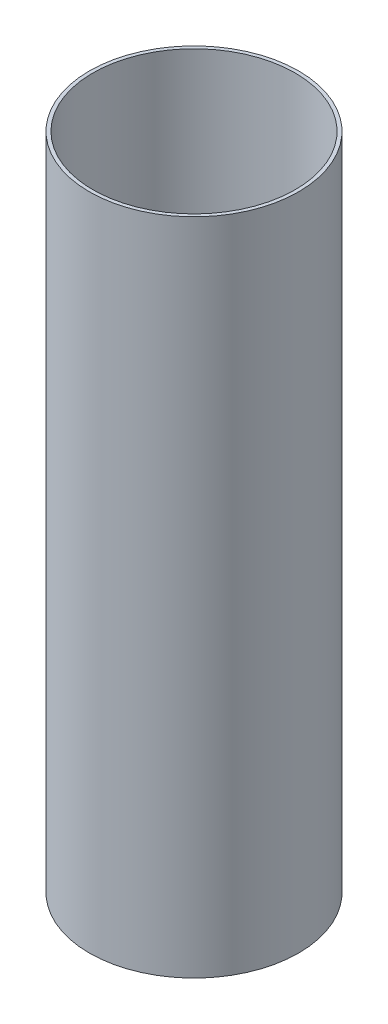
SolidWorks part; units mm, degrees
material "PC High Viscosity"
ref_plane "Front Plane" through (0, 0, 0) normal (0, 0, 1) x (1, 0, 0)
ref_plane "Top Plane" through (0, 0, 0) normal (0, 1, 0) x (1, 0, 0)
ref_plane "Right Plane" through (0, 0, 0) normal (1, 0, 0) x (0, 0, -1)
sketch "Sketch1" plane through (0, 0, 0) normal (0, 0, 1) x (1, 0, 0)
  line L0 (0, 0) -> (0, 600) construction
  line L1 (95.25, 0) -> (92.075, 0)
  line L2 (95.25, 600) -> (95.25, 0)
  line L3 (92.075, 0) -> (92.075, 600)
  line L4 (92.075, 600) -> (95.25, 600)
  line L5 (0, 600) -> (92.075, 600) construction
  line L6 (0, 0) -> (92.075, 0) construction
  dimension "D1" = 92.075
  dimension "D2" = 3.175
  dimension "D3" = 600
revolve "Revolve1" add sketch "Sketch1" angle 360 about L0
ref_plane "Plane1" through (0, 0, 101) normal (0, 0, 1) x (1, 0, 0)
ref_plane "Plane2" through (95.25, 0, 0) normal (1, 0, 0) x (0, 0, -1)
sketch "Sketch3" plane through (95.25, 0, 0) normal (1, 0, 0) x (0, 0, -1)
  line L0 (92.075, 600) -> (-92.075, 600) construction
  circle A0 centre (0, 580.95) radius 3.175
  dimension "D1" = 19.05
  dimension "D2" = 6.35
extrude "Cut-Extrude1" [suppressed] cut sketch "Sketch3" against normal up to surface (3.2298 mm away)
pattern_circular "CirPattern1" [suppressed] count 2 every 180
